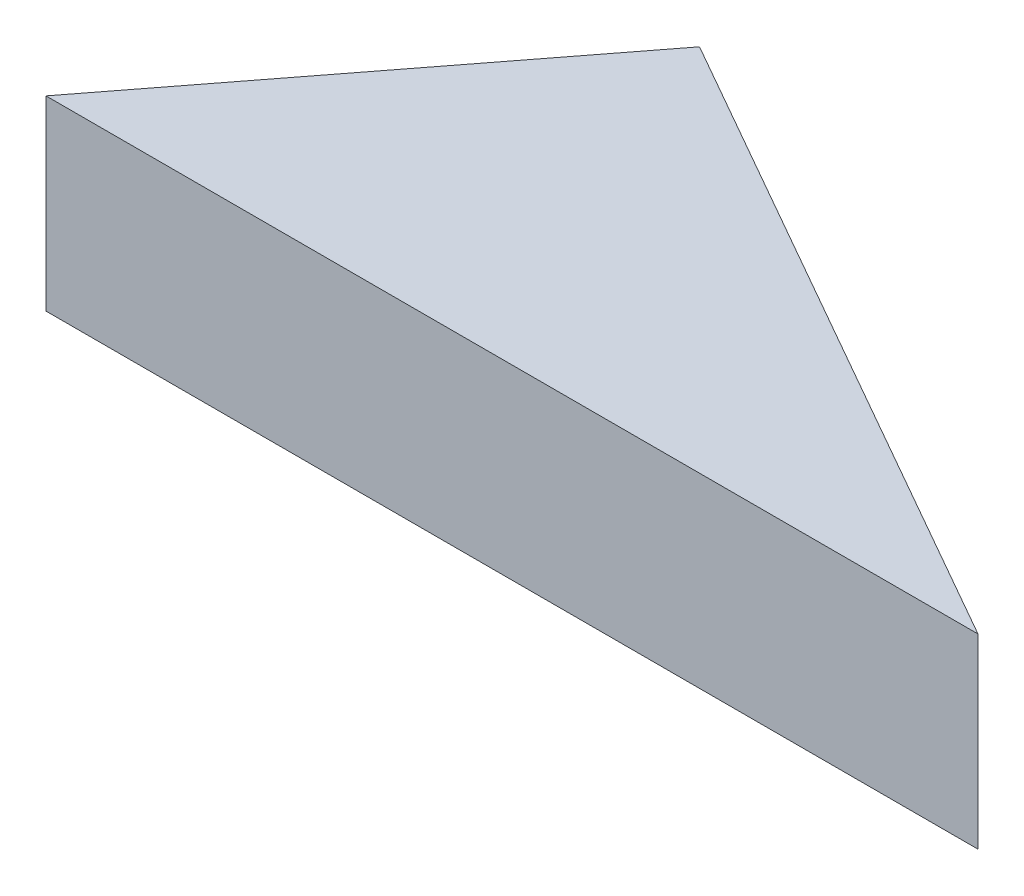
SolidWorks part; units mm, degrees
ref_plane "Front Plane" through (0, 0, 0) normal (0, 0, 1) x (1, 0, 0)
ref_plane "Top Plane" through (0, 0, 0) normal (0, 1, 0) x (1, 0, 0)
ref_plane "Right Plane" through (0, 0, 0) normal (1, 0, 0) x (0, 0, -1)
sketch "Sketch1" plane through (0, 0, 0) normal (0, 1, 0) x (1, 0, 0)
  line L0 (25, 0) -> (-25, 0)
  line L1 (-25, 0) -> (-9.75, 19.81)
  line L2 (-9.75, 19.81) -> (25, 0)
  dimension "D1" = 50
  dimension "D2" = 25
  dimension "D3" = 40
extrude "Boss-Extrude1" add sketch "Sketch1" along normal blind 10
equation "\"A\"= 5"
equation "\"D1@Sketch1\"=\"A\""
equation "\"D2@Sketch1\"=\"A\"/2"
equation "\"B\"=4"
equation "\"D3@Sketch1\"=\"B\""
equation "\"C\"= \"A\" - \"B\""
equation "\"D1@Boss-Extrude1\"=\"C\""
